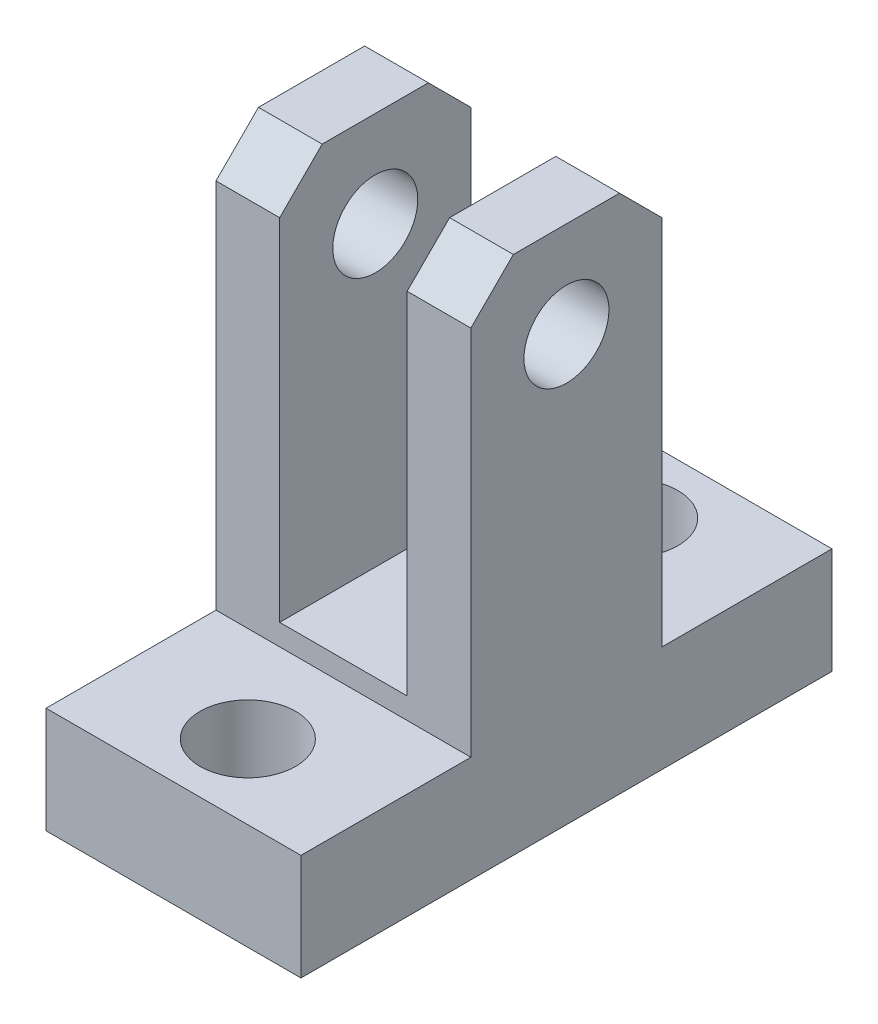
SolidWorks part; units mm, degrees
material "相當於S45C"
ref_plane "Front Plane" through (0, 0, 0) normal (0, 0, 1) x (1, 0, 0)
ref_plane "Top Plane" through (0, 0, 0) normal (0, 1, 0) x (1, 0, 0)
ref_plane "Right Plane" through (0, 0, 0) normal (1, 0, 0) x (0, 0, -1)
ref_plane "Dim.S" through (0, 5, 0) normal (0, 1, 0) x (1, 0, 0)
sketch "Sketch1" plane through (0, 0, 0) normal (1, 0, 0) x (0, 0, -1)
  line L0 (-12.5, 0) -> (12.5, 0)
  line L1 (12.5, 0) -> (12.5, 5)
  line L2 (12.5, 5) -> (4.5, 5)
  line L3 (4.5, 5) -> (4.5, 24.5)
  line L4 (4.5, 24.5) -> (-4.5, 24.5)
  line L5 (-4.5, 24.5) -> (-4.5, 5)
  line L6 (-4.5, 5) -> (-12.5, 5)
  line L7 (-12.5, 5) -> (-12.5, 0)
  line L8 (0, 0) -> (0, 24.5) construction
  line L11 (6.6, 5) -> (-6.6, 5) construction
  dimension "C" = 25
  dimension "T" = 9
  dimension "B" = 24.5
extrude "Boss-Extrude1" add sketch "Sketch1" along normal mid plane 12
sketch "Sketch2" plane through (6, 0, -2) normal (-1, 0, 0) x (0, 0, 1)
  line L0 (2, 20) -> (2, 0) construction
  circle A0 centre (2, 20) radius 2
  dimension "D" = 4
  dimension "H" = 20
extrude "Cut-Extrude1" cut sketch "Sketch2" along normal through all
chamfer "Chamfer1" distance 2 angle 45 2 edges at (0, 24.5, 4.5) (0, 24.5, -4.5)
hole_wizard "Diameter Hole1" positions "Sketch4" profile "Sketch3" hole size "Ø4.5" standard "JIS" end condition through all
sketch "Sketch4" plane through (5.4003, 5, -6.1932) normal (0, -1, 0) x (-1, 0, 0)
  line L0 (-0.5997, -6.1932) -> (5.4003, -6.1932) construction
  line L2 (-0.5997, -18.6932) -> (-0.5997, 6.3068) construction
  point P0 (5.4003, -15.1932)
  point P2 (5.4003, 2.8068)
  dimension "F" = 18
sketch "Sketch3" plane through (0, 5, 9) normal (1, 0, 0) x (0, 0, 1)
  line L0 (0, 0) -> (0, 5)
  line L1 (0, 5) -> (2.25, 5)
  line L2 (2.25, 5) -> (2.25, 0)
  line L5 (2.25, 0) -> (0, 0)
  line L11 (0, -6.35) -> (0, 107.95) construction
  dimension "D_s" = 4.5
  dimension "Thru Hole Depth" = 5
sketch "Sketch5" plane through (0, 0, 0) normal (0, 0, 1) x (1, 0, 0)
  line L0 (0, 0) -> (0, 24.5) construction
  line L1 (-3, 24.5) -> (3, 24.5)
  line L2 (-3, 24.5) -> (-3, 6)
  line L3 (-3, 6) -> (3, 6)
  line L4 (3, 24.5) -> (3, 6)
  line L5 (-6, 24.5) -> (6, 24.5) construction
  line L6 (6.6, 5) -> (-6.6, 5) construction
  dimension "D1" = 1
  dimension "W" = 6
extrude "Cut-Extrude2" cut sketch "Sketch5" against normal through all and the other way through all
sketch "Sketch6" [suppressed] plane through (0, 0, 0) normal (0, 0, 1) x (1, 0, 0)
  line L0 (0, 0) -> (0, 16.5) construction
  line L1 (1.5, 16.5) -> (6, 16.5)
  line L2 (1.5, 16.5) -> (1.5, 6)
  line L3 (1.5, 6) -> (6, 6)
  line L4 (6, 16.5) -> (6, 6)
  line L5 (-6, 16.5) -> (-1.5, 16.5)
  line L6 (-6, 16.5) -> (-6, 6)
  line L7 (-6, 6) -> (-1.5, 6)
  line L8 (-1.5, 16.5) -> (-1.5, 6)
  line L9 (-6, 16.5) -> (6, 16.5) construction
  line L10 (-6, 0) -> (-6, 5) construction
  line L11 (6, 5) -> (6, 0) construction
  line L12 (-6, 16.5) -> (6, 16.5) construction
  line L13 (-6, 16.5) -> (6, 16.5) construction
  line L14 (6.6, 5) -> (-6.6, 5) construction
  dimension "D1" = 1
  dimension "W" = 6
extrude "Cut-Extrude3" [suppressed] cut sketch "Sketch6" against normal through all and the other way through all
equation "\"B@Sketch1\" = \"H@Sketch2\" + \"T@Sketch1\" / 2"
